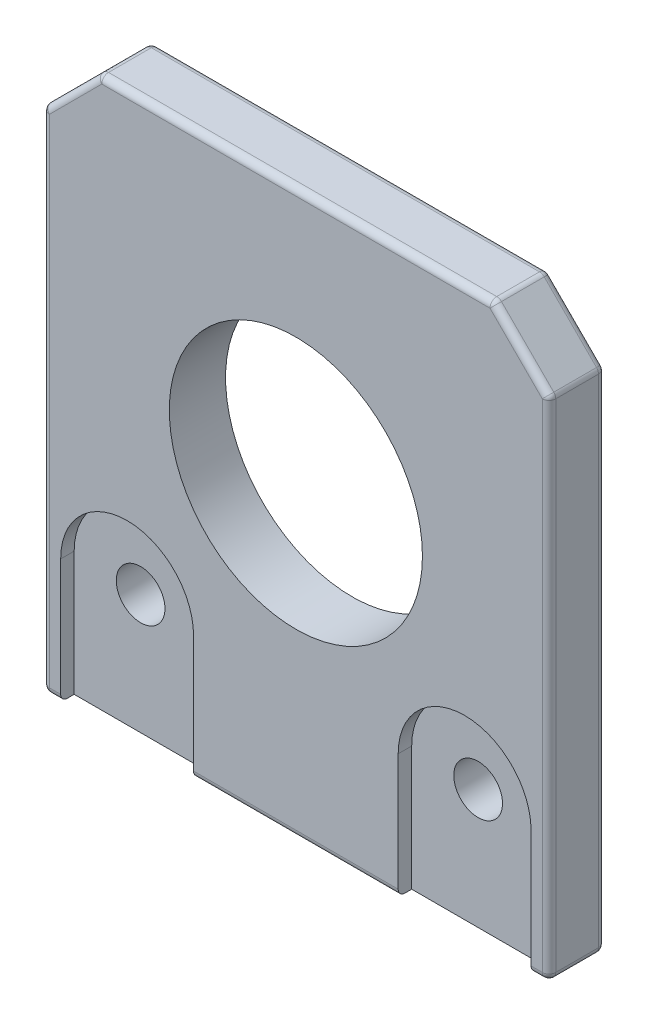
SolidWorks part; units mm, degrees
ref_plane "Front Plane" through (0, 0, 0) normal (0, 0, 1) x (1, 0, 0)
ref_plane "Top Plane" through (0, 0, 0) normal (0, 1, 0) x (1, 0, 0)
ref_plane "Right Plane" through (0, 0, 0) normal (1, 0, 0) x (0, 0, -1)
sketch "Sketch2" plane through (0, 0, 0) normal (0, 1, 0) x (1, 0, 0)
  line L1 (-28.575, 3.175) -> (28.575, 3.175)
  line L2 (-28.575, 3.175) -> (-28.575, -3.175)
  line L3 (-28.575, -3.175) -> (28.575, -3.175)
  line L4 (28.575, 3.175) -> (28.575, -3.175)
  point P4 (0, 3.175)
  point P7 (-28.575, 0)
  dimension "D1" = 6.35
  dimension "D2" = 57.15
extrude "Boss-Extrude1" add sketch "Sketch2" against normal blind 63.5
sketch "Sketch3" plane through (0, 0, 3.175) normal (0, 0, 1) x (1, 0, 0)
  line L2 (-28.575, 0) -> (28.575, 0) construction
  circle A0 centre (0, -28.815) radius 14.2875
  point P2 (0, 0)
  dimension "D1" = 28.815
  dimension "D3" = 28.575
extrude "Cut-Extrude1" cut sketch "Sketch3" against normal through all
chamfer "Chamfer1" distance 6.35 angle 45 2 edges at (-28.575, 0, 0) (28.575, 0, 0)
hole_wizard "M5 Clearance Hole1" positions "Sketch6" profile "Sketch7" hole size "M5" standard "ANSI Metric" end condition through all
sketch "Sketch6" plane through (0, 0, 3.175) normal (0, 0, 1) x (1, 0, 0)
  line L0 (-28.575, -63.5) -> (28.575, -63.5) construction
  line L1 (28.575, -63.5) -> (28.575, -6.35) construction
  point P0 (-19.05, -50)
  point P3 (19.05, -50)
  dimension "D1" = 13.5
  dimension "D2" = 9.525
  dimension "D3" = 38.1
sketch "Sketch7" plane through (-19.05, -50, 3.175) normal (1, 0, 0) x (0, -1, 0)
  line L0 (0, 0) -> (0, 6.35)
  line L1 (0, 6.35) -> (2.75, 6.35)
  line L2 (2.75, 6.35) -> (2.75, 0)
  line L5 (2.75, 0) -> (0, 0)
  line L11 (0, -6.35) -> (0, 107.95) construction
  dimension "Thru Hole Dia." = 5.5
  dimension "Thru Hole Depth" = 6.35
fillet "Fillet1" radius 0.762 18 edges at (0, -63.5, 3.175) (0, -63.5, -3.175) (28.575, -63.5, 0) (28.575, -34.925, 3.175) (28.575, -34.925, -3.175) (-28.575, -63.5, 0) (-28.575, -34.925, -3.175) (-28.575, -34.925, 3.175) (-25.4, -3.175, 3.175) (-28.575, -6.35, 0) (-25.4, -3.175, -3.175) (0, 0, 3.175) (-22.225, 0, 0) (0, 0, -3.175) (22.225, 0, 0) (25.4, -3.175, -3.175) (28.575, -6.35, 0) (25.4, -3.175, 3.175)
sketch "Sketch8" plane through (0, 0, 3.175) normal (0, 0, 1) x (1, 0, 0)
  line L0 (11.55, -63.5) -> (11.55, -49.5)
  line L1 (26.55, -49.5) -> (26.55, -63.5)
  line L2 (11.55, -63.5) -> (26.55, -63.5)
  arc A0 (11.55, -49.5) -> (26.55, -49.5) centre (19.05, -49.5) cw
extrude "Cut-Extrude4" cut sketch "Sketch8" against normal blind 1.524
mirror "Mirror1" about plane through (0, 0, 0) normal (1, 0, 0) of "Cut-Extrude4"
